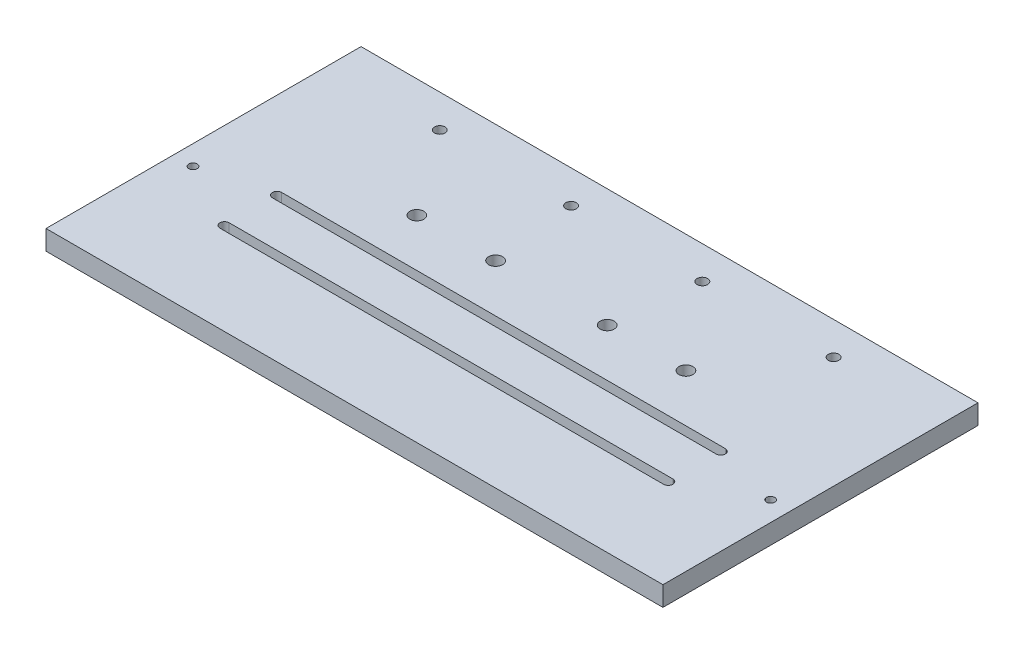
SolidWorks part; units mm, degrees
material "Acrylic (Medium-high impact)"
ref_plane "Front Plane" through (0, 0, 0) normal (0, 0, 1) x (1, 0, 0)
ref_plane "Top Plane" through (0, 0, 0) normal (0, 1, 0) x (1, 0, 0)
ref_plane "Right Plane" through (0, 0, 0) normal (1, 0, 0) x (0, 0, -1)
sketch "Sketch1" plane through (0, 0, 0) normal (0, 1, 0) x (1, 0, 0)
  line L1 (-149.225, -76.2) -> (149.225, -76.2)
  line L2 (-149.225, -76.2) -> (-149.225, 76.2)
  line L3 (-149.225, 76.2) -> (149.225, 76.2)
  line L4 (149.225, -76.2) -> (149.225, 76.2)
  line L5 (-149.225, -76.2) -> (149.225, 76.2) construction
  line L6 (-149.225, 76.2) -> (149.225, -76.2) construction
  line L7 (73.025, -76.2) -> (-130.175, -76.2)
  line L11 (-384.175, -76.2) -> (-231.775, -76.2)
  point P0 (0, 0)
  dimension "D1" = 298.45
  dimension "D2" = 152.4
extrude "Boss-Extrude1" add sketch "Sketch1" along normal mid plane 9.525 contours L1 L4 L3 L2
sketch "Sketch2" [suppressed] plane through (0, 0, 0) normal (0, 1, 0) x (1, 0, 0)
  line L0 (-250.825, -28.575) -> (250.825, -28.575) construction
  line L1 (161.925, -28.575) -> (60.325, -28.575)
  line L2 (161.925, -28.575) -> (161.925, -92.075)
  line L3 (161.925, -92.075) -> (60.325, -92.075)
  line L4 (60.325, -28.575) -> (60.325, -92.075)
  line L5 (0, -5.2388) -> (0, 5.2388) construction
  line L6 (-79.375, -28.575) -> (-168.275, -28.575)
  line L7 (-79.375, -28.575) -> (-79.375, -92.075)
  line L8 (-79.375, -92.075) -> (-168.275, -92.075)
  line L9 (-168.275, -28.575) -> (-168.275, -92.075)
  line L10 (250.825, -28.575) -> (250.825, 28.575) construction
  line L11 (-250.825, -28.575) -> (-250.825, 28.575) construction
  line L12 (-250.825, 28.575) -> (250.825, 28.575) construction
  line L13 (250.825, -28.575) -> (250.825, 28.575) construction
  line L14 (161.925, -28.575) -> (250.825, -28.575)
  line L15 (161.925, -28.575) -> (161.925, -71.755)
  line L16 (161.925, -71.755) -> (250.825, -71.755)
  line L17 (250.825, -28.575) -> (250.825, -71.755)
  line L18 (-250.825, -28.575) -> (-250.825, 28.575) construction
  line L19 (-79.375, -28.575) -> (60.325, -28.575)
  line L20 (-79.375, -28.575) -> (-79.375, -53.975)
  line L21 (-79.375, -53.975) -> (60.325, -53.975)
  line L22 (60.325, -28.575) -> (60.325, -53.975)
  line L23 (-168.275, -28.575) -> (-250.825, -28.575)
  line L24 (-168.275, -28.575) -> (-168.275, -71.755)
  line L25 (-168.275, -71.755) -> (-250.825, -71.755)
  line L26 (-250.825, -28.575) -> (-250.825, -71.755)
  point P19 (60.325, -92.075)
  dimension "D1" = 139.7
  dimension "D2" = 88.9
  dimension "D3" = 82.55
  dimension "D4" = 79.375
  dimension "D5" = 120.65
  dimension "D6" = 43.18
  dimension "D7" = 25.4
  dimension "D8" = 43.18
extrude "Boss-Extrude2" [suppressed] add sketch "Sketch2" along normal mid plane 9.525 contours L6 L9 L8 L7 | L23 L26 L25 L9 | L7 L21 L4 L19 | L17 L14 L2 L16
sketch "Sketch3" [suppressed] plane through (0, 4.7625, 0) normal (0, 1, 0) x (1, 0, 0)
  line L0 (-149.225, 247.65) -> (149.225, 247.65) construction
  line L1 (-98.425, 12.7) -> (98.425, 12.7)
  line L2 (-98.425, 12.7) -> (-98.425, -101.6)
  line L3 (-98.425, -101.6) -> (98.425, -101.6)
  line L4 (98.425, 12.7) -> (98.425, -101.6)
  line L5 (-98.425, 12.7) -> (98.425, -101.6) construction
  line L6 (-98.425, -101.6) -> (98.425, 12.7) construction
  line L7 (-149.225, -247.65) -> (149.225, -247.65) construction
  point P0 (0, -44.45)
  point P7 (0, 247.65)
  point P8 (0, 12.7)
  dimension "D1" = 196.85
  dimension "D2" = 114.3
  dimension "D3" = 203.2
extrude "Cut-Extrude1" [suppressed] cut sketch "Sketch3" against normal through all and the other way through all
sketch "Sketch4" plane through (0, -4.7625, 0) normal (0, -1, 0) x (1, 0, 0)
  line L0 (-107.315, 31.75) -> (107.315, 31.75) construction
  line L1 (-107.315, 33.9979) -> (107.315, 33.9979)
  line L2 (-107.315, 29.5021) -> (107.315, 29.5021)
  line L3 (-107.315, 6.35) -> (107.315, 6.35) construction
  line L4 (-107.315, 8.5979) -> (107.315, 8.5979)
  line L5 (-107.315, 4.1021) -> (107.315, 4.1021)
  arc A0 (-107.315, 33.9979) -> (-107.315, 29.5021) centre (-107.315, 31.75) ccw
  arc A1 (107.315, 29.5021) -> (107.315, 33.9979) centre (107.315, 31.75) ccw
  arc A2 (-107.315, 8.5979) -> (-107.315, 4.1021) centre (-107.315, 6.35) ccw
  arc A3 (107.315, 4.1021) -> (107.315, 8.5979) centre (107.315, 6.35) ccw
  point P0 (-107.315, 31.75)
  point P1 (107.315, 31.75)
  point P3 (107.315, 6.35)
  point P5 (-107.315, 6.35)
  point P10 (0, 31.75)
  point P15 (0, 6.35)
  dimension "D1" = 4.4958
  dimension "D2" = 4.4958
extrude "Cut-Extrude2" cut sketch "Sketch4" against normal through all
sketch "Sketch5" [suppressed] plane through (0, -4.7625, 0) normal (0, -1, 0) x (1, 0, 0)
  line L0 (69.85, 79.375) -> (69.85, -9.525) construction
  line L1 (60.325, 53.975) -> (60.325, 92.075) construction
  line L2 (161.925, 92.075) -> (60.325, 92.075) construction
  line L3 (-247.65, -22.225) -> (247.65, -22.225) construction
  line L4 (69.85, 79.375) -> (69.85, -9.525) construction
  line L5 (72.0979, 79.375) -> (72.0979, -9.525)
  line L6 (67.6021, 79.375) -> (67.6021, -9.525)
  line L7 (-88.9, 79.375) -> (-88.9, -9.525) construction
  line L8 (-79.375, 53.975) -> (-79.375, 92.075) construction
  line L9 (-79.375, 92.075) -> (-168.275, 92.075) construction
  line L10 (-88.9, 79.375) -> (-88.9, -9.525) construction
  line L11 (-86.6521, 79.375) -> (-86.6521, -9.525)
  line L12 (-91.1479, 79.375) -> (-91.1479, -9.525)
  arc A0 (72.0979, 79.375) -> (67.6021, 79.375) centre (69.85, 79.375) ccw
  arc A1 (67.6021, -9.525) -> (72.0979, -9.525) centre (69.85, -9.525) ccw
  arc A2 (-86.6521, 79.375) -> (-91.1479, 79.375) centre (-88.9, 79.375) ccw
  arc A3 (-91.1479, -9.525) -> (-86.6521, -9.525) centre (-88.9, -9.525) ccw
  point P8 (69.85, 34.925)
  point P19 (-88.9, 34.925)
  dimension "D1" = 9.525
  dimension "D2" = 12.7
  dimension "D3" = 12.7
  dimension "D4" = 4.4958
  dimension "D5" = 9.525
  dimension "D6" = 12.7
  dimension "D7" = 12.7
  dimension "D8" = 4.4958
extrude "Cut-Extrude3" [suppressed] cut sketch "Sketch5" against normal through all contours L12 A3 L11 A2 | L6 A1 L5 A0
sketch "Sketch6" [suppressed] plane through (0, 4.7625, 0) normal (0, 1, 0) x (1, 0, 0)
  line L0 (-79.375, -38.1) -> (-79.375, 38.1) construction
  line L1 (-88.9, -50.8) -> (-88.9, 50.8) construction
  line L2 (-88.9, -50.8) -> (88.9, -50.8) construction
  line L3 (-88.9, 50.8) -> (88.9, 50.8) construction
  line L4 (79.375, -38.1) -> (79.375, 38.1) construction
  line L5 (88.9, -50.8) -> (88.9, 50.8) construction
  line L6 (-79.375, -38.1) -> (-79.375, 38.1) construction
  line L7 (-81.6229, -38.1) -> (-81.6229, 38.1)
  line L8 (-77.1271, -38.1) -> (-77.1271, 38.1)
  line L9 (79.375, -38.1) -> (79.375, 38.1) construction
  line L10 (77.1271, -38.1) -> (77.1271, 38.1)
  line L11 (81.6229, -38.1) -> (81.6229, 38.1)
  arc A0 (-81.6229, -38.1) -> (-77.1271, -38.1) centre (-79.375, -38.1) ccw
  arc A1 (-77.1271, 38.1) -> (-81.6229, 38.1) centre (-79.375, 38.1) ccw
  arc A2 (77.1271, -38.1) -> (81.6229, -38.1) centre (79.375, -38.1) ccw
  arc A3 (81.6229, 38.1) -> (77.1271, 38.1) centre (79.375, 38.1) ccw
  point P12 (-79.375, 0)
  point P17 (79.375, 0)
  dimension "D1" = 9.525
  dimension "D2" = 12.7
  dimension "D3" = 12.7
  dimension "D4" = 9.525
  dimension "D5" = 12.7
  dimension "D6" = 12.7
  dimension "D7" = 4.4958
  dimension "D8" = 4.4958
extrude "Cut-Extrude4" [suppressed] cut sketch "Sketch6" against normal through all
sketch "Sketch7" [suppressed] plane through (0, 4.7625, 0) normal (0, 1, 0) x (1, 0, 0)
  point P0 (115.1313, 66.802)
  point P1 (139.827, 42.1063)
  point P3 (-139.827, 42.1063)
  point P5 (-115.1313, 66.802)
hole_wizard "#12 Clearance Hole1" [suppressed] positions "Sketch8" profile "Sketch9" hole size "#12" standard "ANSI Inch"
sketch "Sketch8" [suppressed] plane through (0, 4.7625, 0) normal (0, 1, 0) x (1, 0, 0)
  point P0 (-139.827, 42.1063)
  point P3 (-115.1313, 66.802)
  point P6 (115.1313, 66.802)
  point P9 (139.827, 42.1063)
sketch "Sketch9" plane through (-139.827, 4.7625, -42.1063) normal (1, 0, 0) x (0, 0, 1)
  line L0 (0, 0) -> (0, 18.1964)
  line L1 (0, 18.1964) -> (2.8067, 16.51)
  line L2 (2.8067, 16.51) -> (2.8067, 0)
  line L5 (2.8067, 0) -> (0, 0)
  line L10 (0, 18.1964) -> (-2.8067, 16.51) construction
  line L11 (0, -6.35) -> (0, 107.95) construction
  dimension "Hole Dia." = 5.6134
  dimension "Hole Depth" = 16.51
  dimension "Drill Angle" = 118
sketch "Sketch10" [suppressed] plane through (0, -4.7625, 0) normal (0, -1, 0) x (1, 0, 0)
  point P0 (223.8375, -6.35)
  point P1 (223.8375, 19.05)
  point P3 (-223.8375, 19.05)
  point P5 (-223.8375, -6.35)
hole_wizard "#12 Clearance Hole3" [suppressed] positions "Sketch11" profile "Sketch12" hole size "#12" standard "ANSI Inch"
sketch "Sketch11" plane through (0, -4.7625, 0) normal (0, -1, 0) x (-1, 0, 0)
  point P0 (-223.8375, -19.05)
  point P3 (-223.8375, 6.35)
  point P6 (223.8375, -19.05)
  point P9 (223.8375, 6.35)
sketch "Sketch12" plane through (223.8375, -4.7625, 19.05) normal (1, 0, 0) x (0, 0, -1)
  line L0 (0, 0) -> (0, 18.1964)
  line L1 (0, 18.1964) -> (2.8067, 16.51)
  line L2 (2.8067, 16.51) -> (2.8067, 0)
  line L5 (2.8067, 0) -> (0, 0)
  line L10 (0, 18.1964) -> (-2.8067, 16.51) construction
  line L11 (0, -6.35) -> (0, 107.95) construction
  dimension "Hole Dia." = 5.6134
  dimension "Hole Depth" = 16.51
  dimension "Drill Angle" = 118
sketch "Sketch13" [suppressed] plane through (0, -4.7625, 0) normal (0, -1, 0) x (1, 0, 0)
  point P0 (133.35, -223.8375)
  point P1 (107.95, -223.8375)
  point P3 (-107.95, -223.8375)
  point P5 (-133.35, -223.8375)
  point P7 (133.35, 223.8375)
  point P9 (107.95, 223.8375)
  point P11 (-107.95, 223.8375)
  point P13 (-133.35, 223.8375)
hole_wizard "#12 Clearance Hole2" [suppressed] positions "Sketch14" profile "Sketch15" hole size "#12" standard "ANSI Inch"
sketch "Sketch14" plane through (0, -4.7625, 0) normal (0, -1, 0) x (-1, 0, 0)
  point P0 (107.95, -223.8375)
  point P3 (133.35, -223.8375)
  point P6 (133.35, 223.8375)
  point P9 (107.95, 223.8375)
  point P12 (-133.35, 223.8375)
  point P15 (-107.95, 223.8375)
  point P18 (-133.35, -223.8375)
  point P21 (-107.95, -223.8375)
sketch "Sketch15" plane through (-107.95, -4.7625, 223.8375) normal (1, 0, 0) x (0, 0, -1)
  line L0 (0, 0) -> (0, 18.1964)
  line L1 (0, 18.1964) -> (2.8067, 16.51)
  line L2 (2.8067, 16.51) -> (2.8067, 0)
  line L5 (2.8067, 0) -> (0, 0)
  line L10 (0, 18.1964) -> (-2.8067, 16.51) construction
  line L11 (0, -6.35) -> (0, 107.95) construction
  dimension "Hole Dia." = 5.6134
  dimension "Hole Depth" = 16.51
  dimension "Drill Angle" = 118
sketch "Sketch16" [suppressed] plane through (0, 4.7625, 0) normal (0, 1, 0) x (1, 0, 0)
  line L0 (88.9, -50.8) -> (88.9, 50.8) construction
  line L1 (-88.9, -50.8) -> (-88.9, 50.8) construction
  line L2 (-88.9, -50.8) -> (88.9, -50.8) construction
  point P0 (79.375, -38.1)
  point P1 (-79.375, -38.1)
  dimension "D1" = 9.525
  dimension "D2" = 9.525
  dimension "D3" = 12.7
hole_wizard "#8 Clearance Hole1" [suppressed] positions "Sketch17" profile "Sketch19" hole size "#8" standard "ANSI Inch"
sketch "Sketch17" plane through (0, 4.7625, 0) normal (0, 1, 0) x (1, 0, 0)
  point P0 (79.375, -38.1)
  point P3 (-79.375, -38.1)
sketch "Sketch19" plane through (79.375, 4.7625, 38.1) normal (1, 0, 0) x (0, 0, 1)
  line L0 (0, 0) -> (0, 12.0187)
  line L1 (0, 12.0187) -> (2.2479, 10.668)
  line L2 (2.2479, 10.668) -> (2.2479, 0)
  line L5 (2.2479, 0) -> (0, 0)
  line L10 (0, 12.0187) -> (-2.2479, 10.668) construction
  line L11 (0, -6.35) -> (0, 107.95) construction
  dimension "Hole Dia." = 4.4958
  dimension "Hole Depth" = 10.668
  dimension "Drill Angle" = 118
sketch "Sketch20" [suppressed] plane through (0, -4.7625, 0) normal (0, -1, 0) x (1, 0, 0)
  line L0 (-149.225, 247.65) -> (149.225, 247.65) construction
  line L1 (23.9395, 147.5105) -> (-23.9395, 147.5105)
  line L2 (23.9395, 147.5105) -> (23.9395, 195.3895)
  line L3 (23.9395, 195.3895) -> (-23.9395, 195.3895)
  line L4 (-23.9395, 147.5105) -> (-23.9395, 195.3895)
  line L5 (23.9395, 147.5105) -> (-23.9395, 195.3895) construction
  line L6 (23.9395, 195.3895) -> (-23.9395, 147.5105) construction
  line L8 (38.1, 155.575) -> (-38.1, 155.575) construction
  line L9 (38.1, 155.575) -> (38.1, 187.325) construction
  line L10 (38.1, 187.325) -> (-38.1, 187.325) construction
  line L11 (-38.1, 155.575) -> (-38.1, 187.325) construction
  point P0 (0, 171.45)
  point P7 (0, 247.65)
  point P8 (38.1, 155.575)
  point P9 (38.1, 187.325)
  point P10 (-38.1, 155.575)
  point P11 (-38.1, 187.325)
  point P18 (0, 187.325)
  point P19 (0, 195.3895)
  point P20 (-38.1, 171.45)
  point P21 (-23.9395, 171.45)
  dimension "D1" = 47.879
  dimension "D2" = 47.879
  dimension "D3" = 38.1
  dimension "D4" = 15.875
  dimension "D5" = 76.2
extrude "Cut-Extrude5" [suppressed] cut sketch "Sketch20" against normal through all contours L1 L4 L3 L2
hole_wizard "#10 Clearance Hole1" [suppressed] positions "Sketch21" profile "Sketch22" hole size "#10" standard "ANSI Inch"
sketch "Sketch21" plane through (0, -4.7625, 0) normal (0, -1, 0) x (-1, 0, 0)
  point P0 (-38.1, -155.575)
  point P3 (38.1, -155.575)
  point P6 (38.1, -187.325)
  point P9 (-38.1, -187.325)
sketch "Sketch22" plane through (38.1, -4.7625, 155.575) normal (1, 0, 0) x (0, 0, -1)
  line L0 (0, 0) -> (0, 12.2018)
  line L1 (0, 12.2018) -> (2.5527, 10.668)
  line L2 (2.5527, 10.668) -> (2.5527, 0)
  line L5 (2.5527, 0) -> (0, 0)
  line L10 (0, 12.2018) -> (-2.5527, 10.668) construction
  line L11 (0, -6.35) -> (0, 107.95) construction
  dimension "Hole Dia." = 5.1054
  dimension "Hole Depth" = 10.668
  dimension "Drill Angle" = 118
sketch "Sketch23" [suppressed] plane through (-250.825, 0, 0) normal (-1, 0, 0) x (0, 0, 1)
  line L4 (-28.575, -4.7625) -> (71.755, -4.7625)
  line L5 (71.755, -4.7625) -> (71.755, 4.7625)
  line L6 (71.755, 4.7625) -> (-28.575, 4.7625)
  line L7 (-28.575, 4.7625) -> (-28.575, -4.7625)
  line L8 (-28.575, -4.7625) -> (71.755, -4.7625)
  line L9 (71.755, -4.7625) -> (71.755, 4.7625)
  line L10 (71.755, 4.7625) -> (-28.575, 4.7625)
  line L11 (-28.575, 4.7625) -> (-28.575, -4.7625)
  dimension "D1" = 0
extrude "Boss-Extrude3" [suppressed] add sketch "Sketch23" along normal blind 6.35
mirror "Mirror1" [suppressed] about plane through (0, 0, 0) normal (1, 0, 0)
sketch "Sketch27" [suppressed] plane through (0, 4.7625, 0) normal (0, 1, 0) x (1, 0, 0)
  line L1 (257.175, -71.755) -> (257.175, 28.575) construction
  line L2 (-257.175, 28.575) -> (257.175, 28.575) construction
  point P0 (241.3, 12.7)
  dimension "D1" = 15.875
  dimension "D2" = 15.875
hole_wizard "#10 Clearance Hole2" [suppressed] positions "Sketch28" profile "Sketch30" hole size "#10" standard "ANSI Inch"
sketch "Sketch28" plane through (0, 4.7625, 0) normal (0, 1, 0) x (1, 0, 0)
  point P0 (241.3, 12.7)
sketch "Sketch30" plane through (241.3, 4.7625, -12.7) normal (1, 0, 0) x (0, 0, 1)
  line L0 (0, 0) -> (0, 9.525)
  line L1 (0, 9.525) -> (2.5527, 9.525)
  line L2 (2.5527, 9.525) -> (2.5527, 0)
  line L5 (2.5527, 0) -> (0, 0)
  line L11 (0, -6.35) -> (0, 107.95) construction
  dimension "Thru Hole Dia." = 5.1054
  dimension "Thru Hole Depth" = 9.525
pattern_linear "LPattern1" [suppressed] count 6 spacing 96.52
sketch "Sketch31" plane through (0, 4.7625, 0) normal (0, 1, 0) x (1, 0, 0)
  line L1 (0, -5.2388) -> (0, 5.2388) construction
  line L2 (-149.225, 76.2) -> (149.225, 76.2) construction
  point P0 (-95.25, 60.325)
  dimension "D1" = 15.875
  dimension "D2" = 95.25
hole_wizard "#10 Clearance Hole3" positions "Sketch32" profile "Sketch33" hole size "#10" standard "ANSI Inch" end condition up to next
sketch "Sketch32" plane through (0, 4.7625, 0) normal (0, 1, 0) x (1, 0, 0)
  point P0 (-95.25, 60.325)
sketch "Sketch33" plane through (-95.25, 4.7625, -60.325) normal (1, 0, 0) x (0, 0, 1)
  line L0 (0, 0) -> (0, 9.525)
  line L1 (0, 9.525) -> (2.5527, 9.525)
  line L2 (2.5527, 9.525) -> (2.5527, 0)
  line L5 (2.5527, 0) -> (0, 0)
  line L11 (0, -6.35) -> (0, 107.95) construction
  dimension "Thru Hole Dia." = 5.1054
  dimension "Thru Hole Depth" = 9.525
pattern_linear "LPattern2" count 4 spacing 63.5 along (1, 0, 0) of "#10 Clearance Hole3"
sketch "Sketch34" [suppressed] plane through (0, 4.7625, 0) normal (0, 1, 0) x (1, 0, 0)
  line L0 (0, -5.2388) -> (0, 5.2388) construction
  line L1 (-149.225, 247.65) -> (149.225, 247.65) construction
  point P0 (-63.5, 241.3)
  dimension "D1" = 63.5
  dimension "D2" = 6.35
hole_wizard "#10 Clearance Hole4" [suppressed] positions "Sketch35" profile "Sketch36" hole size "#10" standard "ANSI Inch"
sketch "Sketch35" plane through (0, 4.7625, 0) normal (0, 1, 0) x (1, 0, 0)
  point P0 (-63.5, 241.3)
sketch "Sketch36" plane through (-63.5, 4.7625, -241.3) normal (1, 0, 0) x (0, 0, 1)
  line L0 (0, 0) -> (0, 9.525)
  line L1 (0, 9.525) -> (2.5527, 9.525)
  line L2 (2.5527, 9.525) -> (2.5527, 0)
  line L5 (2.5527, 0) -> (0, 0)
  line L11 (0, -6.35) -> (0, 107.95) construction
  dimension "Thru Hole Dia." = 5.1054
  dimension "Thru Hole Depth" = 9.525
pattern_linear "LPattern3" [suppressed] count 3 spacing 63.5
mirror "Mirror2" [suppressed] about plane through (0, 0, 0) normal (0, 0, 1)
sketch "Sketch37" [suppressed] plane through (0, 4.7625, 0) normal (0, 1, 0) x (1, 0, 0)
  line L0 (-5.2388, 0) -> (5.2388, 0) construction
  line L1 (-149.225, -247.65) -> (-149.225, 247.65) construction
  point P0 (-142.875, 0)
  dimension "D1" = 6.35
hole_wizard "#10 Clearance Hole5" [suppressed] positions "Sketch38" profile "Sketch39" hole size "#10" standard "ANSI Inch"
sketch "Sketch38" plane through (0, 4.7625, 0) normal (0, 1, 0) x (1, 0, 0)
  point P0 (-142.875, 0)
sketch "Sketch39" plane through (-142.875, 4.7625, 0) normal (1, 0, 0) x (0, 0, 1)
  line L0 (0, 0) -> (0, 9.525)
  line L1 (0, 9.525) -> (2.5527, 9.525)
  line L2 (2.5527, 9.525) -> (2.5527, 0)
  line L5 (2.5527, 0) -> (0, 0)
  line L11 (0, -6.35) -> (0, 107.95) construction
  dimension "Thru Hole Dia." = 5.1054
  dimension "Thru Hole Depth" = 9.525
pattern_linear "LPattern4" [suppressed] count 3 spacing 96.52 count 3 spacing 96.52
mirror "Mirror3" [suppressed] about plane through (0, 0, 0) normal (1, 0, 0)
sketch "Sketch40" [suppressed] plane through (0, 4.7625, 0) normal (0, 1, 0) x (1, 0, 0)
  line L0 (-79.375, -53.975) -> (-79.375, -92.075) construction
  line L3 (-88.9, -79.375) -> (-88.9, -9.525) construction
  line L4 (-91.1479, -79.375) -> (-91.1479, -9.525)
  line L5 (-86.6521, -79.375) -> (-86.6521, -9.525)
  line L6 (69.85, -79.375) -> (69.85, -9.525) construction
  line L7 (67.6021, -79.375) -> (67.6021, -9.525)
  line L8 (72.0979, -79.375) -> (72.0979, -9.525)
  line L9 (60.325, -53.975) -> (60.325, -92.075) construction
  line L12 (-79.375, -92.075) -> (-168.275, -92.075) construction
  line L13 (161.925, -92.075) -> (60.325, -92.075) construction
  arc A2 (-91.1479, -79.375) -> (-86.6521, -79.375) centre (-88.9, -79.375) ccw
  arc A3 (-86.6521, -9.525) -> (-91.1479, -9.525) centre (-88.9, -9.525) ccw
  arc A4 (67.6021, -79.375) -> (72.0979, -79.375) centre (69.85, -79.375) ccw
  arc A5 (72.0979, -9.525) -> (67.6021, -9.525) centre (69.85, -9.525) ccw
  point P7 (-88.9, -44.45)
  point P14 (69.85, -44.45)
  dimension "D1" = 9.525
  dimension "D2" = 4.4958
  dimension "D3" = 4.4958
  dimension "D4" = 9.525
  dimension "D5" = 12.7
  dimension "D6" = 12.7
  dimension "D7" = 69.85
  dimension "D8" = 69.85
extrude "Cut-Extrude6" [suppressed] cut sketch "Sketch40" against normal up to next
sketch "Sketch41" [suppressed] plane through (0, -4.7625, 0) normal (0, -1, 0) x (1, 0, 0)
  point P0 (120.65, -32.5755)
  point P1 (-120.65, -32.5755)
  point P3 (-120.65, 121.4755)
  point P5 (120.65, 121.4755)
hole_wizard "#10 Clearance Hole6" [suppressed] positions "Sketch42" profile "Sketch43" hole size "#10" standard "ANSI Inch"
sketch "Sketch42" plane through (0, 4.7625, 0) normal (0, 1, 0) x (1, 0, 0)
  point P0 (120.65, 32.5755)
  point P3 (120.65, -121.4755)
  point P6 (-120.65, -121.4755)
  point P9 (-120.65, 32.5755)
sketch "Sketch43" plane through (120.65, 4.7625, -32.5755) normal (1, 0, 0) x (0, 0, 1)
  line L0 (0, 0) -> (0, 9.525)
  line L1 (0, 9.525) -> (2.5527, 9.525)
  line L2 (2.5527, 9.525) -> (2.5527, 0)
  line L5 (2.5527, 0) -> (0, 0)
  line L11 (0, -6.35) -> (0, 107.95) construction
  dimension "Thru Hole Dia." = 5.1054
  dimension "Thru Hole Depth" = 9.525
sketch "Sketch44" [suppressed] plane through (0, 4.7625, 0) normal (0, 1, 0) x (1, 0, 0)
  line L0 (0, -5.2388) -> (0, 5.2388) construction
  line L2 (120.65, 32.5755) -> (-120.65, 32.5755) construction
  line L3 (120.65, -121.4755) -> (-120.65, -121.4755) construction
  point P0 (76.2, 32.5755)
  point P1 (0, 32.5755)
  point P2 (-76.2, 32.5755)
  point P3 (76.2, -121.4755)
  point P4 (0, -121.4755)
  point P5 (-76.2, -121.4755)
  dimension "D1" = 76.2
  dimension "D2" = 76.2
hole_wizard "#10 Clearance Hole7" [suppressed] positions "Sketch45" profile "Sketch46" hole size "#10" standard "ANSI Inch"
sketch "Sketch45" plane through (0, 4.7625, 0) normal (0, 1, 0) x (1, 0, 0)
  point P0 (76.2, 32.5755)
  point P3 (0, 32.5755)
  point P6 (-76.2, 32.5755)
  point P9 (76.2, -121.4755)
  point P12 (0, -121.4755)
  point P15 (-76.2, -121.4755)
sketch "Sketch46" plane through (76.2, 4.7625, -32.5755) normal (1, 0, 0) x (0, 0, 1)
  line L0 (0, 0) -> (0, 9.525)
  line L1 (0, 9.525) -> (2.5527, 9.525)
  line L2 (2.5527, 9.525) -> (2.5527, 0)
  line L5 (2.5527, 0) -> (0, 0)
  line L11 (0, -6.35) -> (0, 107.95) construction
  dimension "Thru Hole Dia." = 5.1054
  dimension "Thru Hole Depth" = 9.525
sketch "Sketch47" [suppressed] plane through (0, 4.7625, 0) normal (0, 1, 0) x (1, 0, 0)
  line L1 (-142.875, 0) -> (-142.875, -96.52) construction
  line L2 (142.875, 0) -> (142.875, -96.52) construction
  point P0 (-142.875, -71.12)
  point P1 (142.875, -25.4)
  point P2 (-142.875, -25.4)
  point P3 (142.875, -71.12)
  dimension "D1" = 25.4
  dimension "D2" = 25.4
  dimension "D3" = 25.4
  dimension "D4" = 25.4
hole_wizard "#10 Clearance Hole8" [suppressed] positions "Sketch48" profile "Sketch49" hole size "#10" standard "ANSI Inch"
sketch "Sketch48" plane through (0, 4.7625, 0) normal (0, 1, 0) x (1, 0, 0)
  point P0 (-142.875, -71.12)
  point P3 (142.875, -25.4)
  point P7 (-142.875, -25.4)
  point P10 (142.875, -71.12)
sketch "Sketch49" plane through (-142.875, 4.7625, 71.12) normal (1, 0, 0) x (0, 0, 1)
  line L0 (0, 0) -> (0, 9.525)
  line L1 (0, 9.525) -> (2.5527, 9.525)
  line L2 (2.5527, 9.525) -> (2.5527, 0)
  line L5 (2.5527, 0) -> (0, 0)
  line L11 (0, -6.35) -> (0, 107.95) construction
  dimension "Thru Hole Dia." = 5.1054
  dimension "Thru Hole Depth" = 9.525
sketch "Sketch50" [suppressed] plane through (0, 0, 0) normal (0, 1, 0) x (1, 0, 0)
  line L1 (-209.55, -50.8) -> (209.55, -50.8)
  line L2 (-209.55, -50.8) -> (-209.55, 50.8)
  line L3 (-209.55, 50.8) -> (209.55, 50.8)
  line L4 (209.55, -50.8) -> (209.55, 50.8)
  line L5 (-209.55, -50.8) -> (209.55, 50.8) construction
  line L6 (-209.55, 50.8) -> (209.55, -50.8) construction
  point P0 (0, 0)
  dimension "D1" = 419.1
  dimension "D2" = 101.6
extrude "Boss-Extrude4" [suppressed] add sketch "Sketch50" along normal blind 9.525
sketch "Sketch51" [suppressed] plane through (0, 0, 0) normal (0, -1, 0) x (1, 0, 0)
  line L0 (144.78, -12.7) -> (144.78, -50.8) construction
  line L1 (152.7175, -12.7) -> (152.7175, -50.8)
  line L2 (136.8425, -12.7) -> (136.8425, -50.8)
  line L3 (209.55, -50.8) -> (-209.55, -50.8) construction
  line L4 (209.55, 50.8) -> (209.55, -50.8) construction
  line L5 (48.26, -50.8) -> (48.26, -12.7) construction
  line L7 (40.3225, -50.8) -> (40.3225, -12.7)
  line L8 (56.1975, -50.8) -> (56.1975, -12.7)
  arc A0 (152.7175, -12.7) -> (136.8425, -12.7) centre (144.78, -12.7) ccw
  arc A1 (136.8425, -50.8) -> (152.7175, -50.8) centre (144.78, -50.8) ccw
  arc A2 (40.3225, -50.8) -> (56.1975, -50.8) centre (48.26, -50.8) ccw
  arc A3 (56.1975, -12.7) -> (40.3225, -12.7) centre (48.26, -12.7) ccw
  point P2 (144.78, -31.75)
  point P7 (48.26, -31.75)
  dimension "D1" = 38.1
  dimension "D2" = 64.77
  dimension "D3" = 15.875
  dimension "D4" = 15.875
  dimension "D5" = 96.52
extrude "Cut-Extrude7" [suppressed] cut sketch "Sketch51" against normal up to next
mirror "Mirror4" [suppressed] about plane through (0, 0, 0) normal (1, 0, 0)
sketch "Sketch52" [suppressed] plane through (0, 4.7625, 0) normal (0, 1, 0) x (1, 0, 0)
  line L0 (-79.375, -92.075) -> (-168.275, -92.075) construction
  line L1 (161.925, -92.075) -> (60.325, -92.075) construction
  point P0 (-123.825, -38.1)
  point P1 (111.125, -38.1)
  point P4 (-123.825, -92.075)
  point P7 (111.125, -92.075)
  dimension "D1" = 53.975
hole_wizard "#10 Clearance Hole9" [suppressed] positions "Sketch53" profile "Sketch54" hole size "#10" standard "ANSI Inch"
sketch "Sketch53" plane through (0, 4.7625, 0) normal (0, 1, 0) x (1, 0, 0)
  point P0 (-123.825, -38.1)
  point P3 (111.125, -38.1)
sketch "Sketch54" plane through (-123.825, 4.7625, 38.1) normal (1, 0, 0) x (0, 0, 1)
  line L0 (0, 0) -> (0, 9.525)
  line L1 (0, 9.525) -> (2.5527, 9.525)
  line L2 (2.5527, 9.525) -> (2.5527, 0)
  line L5 (2.5527, 0) -> (0, 0)
  line L11 (0, -6.35) -> (0, 107.95) construction
  dimension "Thru Hole Dia." = 5.1054
  dimension "Thru Hole Depth" = 9.525
sketch "Sketch55" [suppressed] plane through (0, 0, 0) normal (0, -1, 0) x (1, 0, 0)
  line L0 (111.125, 34.925) -> (111.125, -34.925) construction
  line L1 (113.792, 34.925) -> (113.792, -34.925)
  line L2 (108.458, 34.925) -> (108.458, -34.925)
  line L3 (-123.825, 34.925) -> (-123.825, -34.925) construction
  line L4 (209.55, 50.8) -> (209.55, -50.8) construction
  line L5 (-121.158, 34.925) -> (-121.158, -34.925)
  line L6 (-126.492, 34.925) -> (-126.492, -34.925)
  line L7 (-209.55, -50.8) -> (-209.55, 50.8) construction
  arc A0 (113.792, 34.925) -> (108.458, 34.925) centre (111.125, 34.925) ccw
  arc A1 (108.458, -34.925) -> (113.792, -34.925) centre (111.125, -34.925) ccw
  arc A2 (-121.158, 34.925) -> (-126.492, 34.925) centre (-123.825, 34.925) ccw
  arc A3 (-126.492, -34.925) -> (-121.158, -34.925) centre (-123.825, -34.925) ccw
  point P2 (111.125, 0)
  point P11 (209.55, 0)
  point P12 (-123.825, 0)
  dimension "D1" = 5.334
  dimension "D2" = 69.85
  dimension "D3" = 98.425
  dimension "D4" = 85.725
  dimension "D5" = 5.334
  dimension "D6" = 69.85
extrude "Cut-Extrude8" [suppressed] cut sketch "Sketch55" against normal up to next contours L6 A3 L5 A2 | L2 A1 L1 A0
sketch "Sketch56" [suppressed] plane through (0, 4.7625, 0) normal (0, 1, 0) x (1, 0, 0)
  line L0 (-257.175, -71.755) -> (-257.175, 28.575) construction
  line L1 (-168.275, -71.755) -> (-257.175, -71.755) construction
  line L2 (257.175, -71.755) -> (257.175, 28.575) construction
  line L3 (161.925, -71.755) -> (257.175, -71.755) construction
  point P0 (-234.95, -62.23)
  point P5 (234.95, -62.23)
  dimension "D1" = 22.225
  dimension "D2" = 9.525
  dimension "D3" = 22.225
  dimension "D4" = 9.525
hole_wizard "#10-32 Tapped Hole2" [suppressed] positions "Sketch57" profile "Sketch58" tap size "#10-32" standard "ANSI Inch"
sketch "Sketch57" plane through (0, 4.7625, 0) normal (0, 1, 0) x (1, 0, 0)
  point P0 (234.95, -62.23)
  point P3 (-234.95, -62.23)
sketch "Sketch58" plane through (234.95, 4.7625, 62.23) normal (1, 0, 0) x (0, 0, 1)
  line L0 (0, 0) -> (0, 9.525)
  line L1 (0, 9.525) -> (2.0193, 9.525)
  line L2 (2.0193, 9.525) -> (2.0193, 0)
  line L5 (2.0193, 0) -> (0, 0)
  line L11 (0, -6.35) -> (0, 107.95) construction
  dimension "Thru Tap Drill Dia." = 4.0386
  dimension "Thru Tap Drill Depth" = 9.525
sketch "Sketch59" plane through (0, 4.7625, 0) normal (0, 1, 0) x (1, 0, 0)
  line L0 (-149.225, -76.2) -> (149.225, -76.2) construction
  line L1 (149.225, -76.2) -> (149.225, 76.2) construction
  line L2 (-149.225, -76.2) -> (-149.225, 76.2) construction
  point P0 (139.7, -14.605)
  point P1 (-139.7, -14.605)
  dimension "D1" = 61.595
  dimension "D2" = 9.525
  dimension "D3" = 9.525
hole_wizard "#10-32 Tapped Hole1" positions "Sketch60" profile "Sketch62" tap size "#10-32" standard "ANSI Inch" end condition through all
sketch "Sketch60" plane through (0, 4.7625, 0) normal (0, 1, 0) x (1, 0, 0)
  point P0 (-139.7, -14.605)
  point P3 (139.7, -14.605)
sketch "Sketch62" plane through (-139.7, 4.7625, 14.605) normal (1, 0, 0) x (0, 0, 1)
  line L0 (0, 0) -> (0, 9.525)
  line L1 (0, 9.525) -> (2.0193, 9.525)
  line L2 (2.0193, 9.525) -> (2.0193, 0)
  line L5 (2.0193, 0) -> (0, 0)
  line L11 (0, -6.35) -> (0, 107.95) construction
  dimension "Thru Tap Drill Dia." = 4.0386
  dimension "Thru Tap Drill Depth" = 9.525
cosmetic thread "Hole Thread1" parameters "D2"=4.826
cosmetic thread "Hole Thread2" parameters "D2"=4.826
sketch "Sketch63" plane through (0, 4.7625, 0) normal (0, 1, 0) x (1, 0, 0)
  line L0 (-149.225, 76.2) -> (149.225, 76.2) construction
  line L1 (-149.225, -76.2) -> (-149.225, 76.2) construction
  point P0 (-65.0875, 19.05)
  point P1 (-26.9875, 19.05)
  dimension "D1" = 38.1
  dimension "D2" = 57.15
  dimension "D3" = 84.1375
hole_wizard "1/4 Clearance Hole1" positions "Sketch64" profile "Sketch65" hole size "1/4" standard "ANSI Inch" end condition through all
sketch "Sketch64" plane through (0, 4.7625, 0) normal (0, 1, 0) x (1, 0, 0)
  point P0 (-65.0875, 19.05)
  point P3 (-26.9875, 19.05)
sketch "Sketch65" plane through (-65.0875, 4.7625, -19.05) normal (1, 0, 0) x (0, 0, 1)
  line L0 (0, 0) -> (0, 9.525)
  line L1 (0, 9.525) -> (3.3782, 9.525)
  line L2 (3.3782, 9.525) -> (3.3782, 0)
  line L5 (3.3782, 0) -> (0, 0)
  line L11 (0, -6.35) -> (0, 107.95) construction
  dimension "Thru Hole Dia." = 6.7564
  dimension "Thru Hole Depth" = 9.525
mirror "Mirror5" about plane through (0, 0, 0) normal (1, 0, 0) of "1/4 Clearance Hole1"
sketch "Sketch66" [suppressed] plane through (0, 4.7625, 0) normal (0, 1, 0) x (1, 0, 0)
  line L0 (-128.905, -44.45) -> (128.905, -44.45) construction
  line L1 (98.425, -101.6) -> (98.425, 12.7) construction
  line L2 (149.225, -247.65) -> (149.225, 247.65) construction
  line L3 (0, -5.2388) -> (0, 5.2388) construction
  point P4 (98.425, -44.45)
  point P7 (0, -44.45)
  dimension "D1" = 20.32
hole_wizard "1/4-20 Tapped Hole1" [suppressed] positions "Sketch67" profile "Sketch68" tap size "1/4-20" standard "ANSI Inch"
sketch "Sketch67" plane through (0, 4.7625, 0) normal (0, 1, 0) x (1, 0, 0)
  point P0 (-128.905, -44.45)
  point P3 (128.905, -44.45)
sketch "Sketch68" plane through (-128.905, 4.7625, 44.45) normal (1, 0, 0) x (0, 0, 1)
  line L0 (0, 0) -> (0, 9.525)
  line L1 (0, 9.525) -> (2.5527, 9.525)
  line L2 (2.5527, 9.525) -> (2.5527, 0)
  line L5 (2.5527, 0) -> (0, 0)
  line L11 (0, -6.35) -> (0, 107.95) construction
  dimension "Thru Tap Drill Dia." = 5.1054
  dimension "Thru Tap Drill Depth" = 9.525
